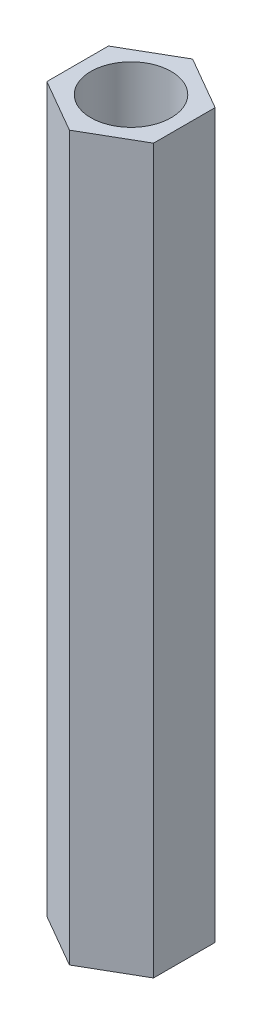
SolidWorks part; units mm, degrees
material "黄铜"
ref_plane "前视基准面" through (0, 0, 0) normal (0, 0, 1) x (1, 0, 0)
ref_plane "上视基准面" through (0, 0, 0) normal (0, 1, 0) x (1, 0, 0)
ref_plane "右视基准面" through (0, 0, 0) normal (1, 0, 0) x (0, 0, -1)
other "Configuration Table"
sketch "草图1" plane through (0, 0, 0) normal (0, 1, 0) x (1, 0, 0)
  line L1 (0, 2.3) -> (-1.9919, 1.15)
  line L2 (-1.9919, 1.15) -> (-1.9919, -1.15)
  line L3 (-1.9919, -1.15) -> (0, -2.3)
  line L4 (0, -2.3) -> (1.9919, -1.15)
  line L5 (1.9919, -1.15) -> (1.9919, 1.15)
  line L6 (1.9919, 1.15) -> (0, 2.3)
  circle A0 centre (0, 0) radius 1.5
  circle A1 centre (0, 0) radius 1.9919 construction
  dimension "D1" = 3
  dimension "D2" = 4.6
extrude "凸台-拉伸1" add sketch "草图1" along normal blind 27
